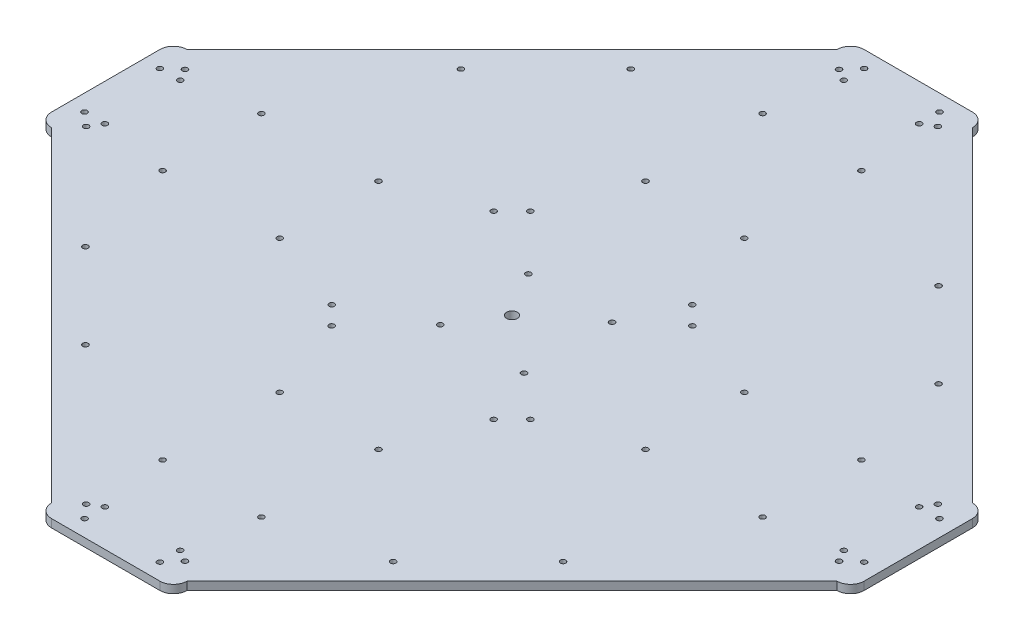
SolidWorks part; units mm, degrees
material "Acrylic (Medium-high impact)"
ref_plane "Front" through (0, 0, 0) normal (0, 0, 1) x (1, 0, 0)
ref_plane "Top" through (0, 0, 0) normal (0, 1, 0) x (1, 0, 0)
ref_plane "Right" through (0, 0, 0) normal (1, 0, 0) x (0, 0, -1)
sketch "Sketch1" plane through (0, 0, 0) normal (0, 1, 0) x (1, 0, 0)
  line L0 (-110, 50) -> (-300, 50)
  line L1 (280, -50) -> (90, -50)
  line L2 (290, -40) -> (290, 40)
  line L3 (280, 50) -> (90, 50)
  line L4 (-310, -40) -> (-310, 40)
  line L5 (-60, 100) -> (-110, 50)
  line L6 (90, 50) -> (40, 100)
  line L7 (30, -300) -> (-50, -300)
  line L8 (40, -290) -> (40, -100)
  line L9 (30, 300) -> (-50, 300)
  line L10 (-60, -290) -> (-60, -100)
  line L11 (90, -50) -> (40, -100)
  line L12 (-60, -100) -> (-110, -50)
  line L16 (-110, -50) -> (-300, -50)
  line L18 (40, 100) -> (40, 290)
  line L19 (-60, 100) -> (-60, 290)
  arc A0 (-50, 300) -> (-60, 290) centre (-50, 290) ccw
  arc A1 (40, 290) -> (30, 300) centre (30, 290) ccw
  arc A2 (290, 40) -> (280, 50) centre (280, 40) ccw
  arc A3 (280, -50) -> (290, -40) centre (280, -40) ccw
  arc A4 (30, -300) -> (40, -290) centre (30, -290) ccw
  arc A5 (-50, -300) -> (-60, -290) centre (-50, -290) cw
  arc A6 (-300, -50) -> (-310, -40) centre (-300, -40) cw
  arc A7 (-300, 50) -> (-310, 40) centre (-300, 40) ccw
  point P0 (0, 0)
  point P1 (8.4315, 46.1032)
  point P2 (128.4315, 46.1032)
  point P3 (8.4315, -56.5685)
  point P4 (128.4315, -56.5685)
  point P5 (0, 0)
  point P10 (0, 0)
  point P15 (-60, -50)
  point P17 (-60, 50)
  point P18 (-56.5685, -56.5685)
  point P23 (56.5685, 56.5685)
  point P25 (40, -50)
  point P28 (40, 50)
  point P31 (-60, 300)
  point P34 (40, 300)
  point P37 (290, 50)
  point P43 (40, -300)
  point P48 (-310, -50)
  point P51 (-310, 50)
  dimension "D1" = 600
  dimension "D5" = 10
  dimension "D2" = 100
  dimension "D3" = 100
  dimension "D4" = 600
  dimension "D6" = 190
  dimension "D7" = 190
  dimension "D8" = 190
  dimension "D9" = 190
extrude "Boss-Extrude1" add sketch "Sketch1" along normal blind 6
sketch "Sketch4" plane through (0, 6, 0) normal (0, 1, 0) x (1, 0, 0)
  line L0 (-10, 300) -> (-10, -432.1332) construction
  line L1 (30, 300) -> (-50, 300) construction
  line L2 (-338.2481, 0) -> (378.576, 0) construction
  circle A0 centre (-10, 0) radius 0.4957
extrude "Cut-Extrude3" cut sketch "Sketch4" against normal blind 10
sketch "Sketch5" plane through (0, 6, 0) normal (0, 1, 0) x (1, 0, 0)
  line L0 (-300, 50) -> (-60, 290)
  line L1 (-250, 50) -> (-60, 240)
  line L2 (-110, 50) -> (-300, 50) construction
  line L3 (-60, 100) -> (-60, 290) construction
  line L4 (-60, 240) -> (-60, 290)
  line L5 (-250, 50) -> (-300, 50)
  line L6 (40, 290) -> (280, 50)
  line L7 (280, 50) -> (230, 50)
  line L8 (230, 50) -> (40, 240)
  line L9 (40, 240) -> (40, 290)
  line L10 (280, -50) -> (40, -290)
  line L11 (40, -290) -> (40, -240)
  line L12 (40, -240) -> (230, -49.078)
  line L13 (230, -49.078) -> (280, -50)
  line L14 (-300, -50) -> (-60, -290)
  line L15 (-60, -290) -> (-60, -240)
  line L16 (-60, -240) -> (-250, -50)
  line L17 (-250, -50) -> (-300, -50)
  point P25 (-10, 2)
  dimension "D1" = 50
  dimension "D2" = 50
  dimension "D3" = 50
  dimension "D4" = 50
  dimension "D5" = 50
  dimension "D6" = 50
  dimension "D7" = 50
  dimension "D8" = 50
extrude "Boss-Extrude3" add sketch "Sketch5" against normal blind 6
sketch "Sketch6" plane through (0, 6, 0) normal (0, 1, 0) x (1, 0, 0)
  circle A0 centre (-37.8241, 287.837) radius 2
  circle A1 centre (-37.8241, 272.837) radius 2
  circle A4 centre (-46.4831, 221.5369) radius 2
  circle A5 centre (-46.4831, 135.0679) radius 2
  circle A6 centre (-69.8176, 73.3345) radius 2
  circle A7 centre (49.8176, 73.3345) radius 2
  circle A8 centre (26.4831, 135.0679) radius 2
  circle A9 centre (26.4831, 221.5369) radius 2
  circle A10 centre (191.3604, 113.6396) radius 2
  circle A11 centre (128.6396, 176.3604) radius 2
  circle A12 centre (17.8241, 272.837) radius 2
  circle A13 centre (17.8241, 287.837) radius 2
  circle A14 centre (-10, 0) radius 4
  dimension "D1" = 4
  dimension "D2" = 4
  dimension "D4" = 8
  dimension "D8" = 4
  dimension "D9" = 4
  dimension "D10" = 4
  dimension "D3" = 15
extrude "Cut-Extrude4" cut sketch "Sketch6" against normal blind 12
pattern_circular "CirPattern1" count 4 over 360 about axis through (-10, 0, 0) along (0, 1, 0) of "Cut-Extrude4"
sketch "Sketch7" plane through (0, 6, 0) normal (0, 1, 0) x (1, 0, 0)
  line L0 (40, 240) -> (230, 50) construction
  line L1 (40, 100) -> (40, 240) construction
  line L2 (90, 50) -> (40, 100) construction
  line L3 (230, 50) -> (90, 50) construction
  line L4 (90, -50) -> (229.0824, -50) construction
  line L5 (229.0824, -50) -> (40, -240) construction
  line L6 (40, -100) -> (90, -50) construction
  line L7 (40, -240) -> (40, -100) construction
  line L8 (-60, 240) -> (-60, 100) construction
  line L9 (-250, 50) -> (-60, 240) construction
  line L10 (-60, 100) -> (-110, 50) construction
  line L11 (-110, 50) -> (-250, 50) construction
  line L12 (-110, -50) -> (-60, -100) construction
  line L13 (-250, -50) -> (-110, -50) construction
  line L14 (-60, -240) -> (-250, -50) construction
  line L15 (-60, -100) -> (-60, -240) construction
  line L16 (40, 240) -> (230, 50)
  line L17 (40, 100) -> (40, 240)
  line L18 (90, 50) -> (40, 100)
  line L19 (230, 50) -> (90, 50)
  line L20 (90, -50) -> (229.0824, -50)
  line L21 (229.0824, -50) -> (40, -240)
  line L22 (40, -100) -> (90, -50)
  line L23 (40, -240) -> (40, -100)
  line L24 (-60, 240) -> (-60, 100)
  line L25 (-250, 50) -> (-60, 240)
  line L26 (-60, 100) -> (-110, 50)
  line L27 (-110, 50) -> (-250, 50)
  line L28 (-110, -50) -> (-60, -100)
  line L29 (-250, -50) -> (-110, -50)
  line L30 (-60, -240) -> (-250, -50)
  line L31 (-60, -100) -> (-60, -240)
extrude "Boss-Extrude4" add sketch "Sketch7" against normal up to surface (6 mm away) up to face at (63.3345, 0, -57.8176)
sketch "Sketch8" plane through (0, 0, 0) normal (0, -1, 0) x (-1, 0, 0)
  circle A0 centre (-279, 20) radius 2.5
  circle A1 centre (-279, -20) radius 2.5
extrude "Cut-Extrude5" [suppressed] cut sketch "Sketch8" against normal blind 144
pattern_circular "CirPattern2" [suppressed] count 4 over 360
sketch "Sketch9" plane through (0, 0, 0) normal (0, -1, 0) x (-1, 0, 0)
  circle A0 centre (-255, -20) radius 2.5
  circle A1 centre (-255, 20) radius 2.5
extrude "Cut-Extrude6" [suppressed] cut sketch "Sketch9" against normal blind 144
pattern_circular "CirPattern3" [suppressed] count 4 over 360
sketch "Sketch10" plane through (0, 6, 0) normal (0, 1, 0) x (1, 0, 0)
  line L0 (-310, 40) -> (-310, -40) construction
  line L1 (-50, -300) -> (30, -300) construction
  point P0 (-57, 33)
  point P1 (37, 33)
  point P2 (-57, -33)
  point P3 (37, -33)
  dimension "D1" = 94
  dimension "D2" = 66
  dimension "D3" = 253
  dimension "D4" = 267
ref_plane "Plane1" through (-10, 0, 0) normal (1, 0, 0) x (0, 0, -1)
ref_plane "Plane2" through (0, 0, 0) normal (0, 0, 1) x (1, 0, 0)
ref_plane "Plane3" through (-10, 0, 0) normal (-1, 0, 0) x (0, 0, 1)
sketch "Sketch11" plane through (0, 6, 0) normal (0, 1, 0) x (1, 0, 0)
  point P0 (32.7129, 23.7813)
  point P1 (-226.182, -59.3281)
  point P3 (-30.4306, -32.5)
  point P4 (31.3831, -32.5)
  point P6 (-29.1008, 23.7813)
sketch "Sketch23" plane through (0, 0, 0) normal (0, -1, 0) x (1, 0, 0)
  point P0 (-10, -24.0416)
  point P1 (-34.0416, 0)
  point P2 (-10, 24.0416)
  point P3 (14.0416, 0)
hole_wizard "Ø4.0mm Dowel Hole3" [suppressed] positions "Sketch26" profile "Sketch27" hole size "Ø4.0" standard "ANSI Metric"
sketch "Sketch26" plane through (0, 4, 0) normal (0, 1, 0) x (1, 0, 0)
  point P0 (-10, 24.0416)
  point P2 (-34.0416, 0)
  point P4 (14.0416, 0)
  point P6 (-10, -24.0416)
sketch "Sketch27" plane through (-10, 4, -24.0416) normal (1, 0, 0) x (0, 0, 1)
  line L0 (0, 0) -> (0, 99.5117)
  line L1 (0, 99.5117) -> (2, 98.31)
  line L2 (2, 98.31) -> (2, 0)
  line L5 (2, 0) -> (0, 0)
  line L10 (0, 99.5117) -> (-2, 98.31) construction
  line L11 (0, -6.35) -> (0, 107.95) construction
  dimension "Hole Dia." = 4
  dimension "Hole Depth" = 98.31
  dimension "Drill Angle" = 118
ref_plane "Plane4" through (-10, 0, 0) normal (-1, 0, 0) x (0, 0, 1)
sketch "Sketch28" plane through (0, 0, 0) normal (0, -1, 0) x (1, 0, 0)
  point P0 (-288, 36.4831)
  point P1 (-288, -36.4831)
  point P2 (-46.4831, -278)
  point P3 (26.4831, -278)
  point P4 (268, -36.4831)
  point P5 (268, 36.4831)
  point P6 (-46.4831, 278)
  point P7 (26.4831, 278)
hole_wizard "Ø4.0mm Dowel Hole4" positions "Sketch29" profile "Sketch30" hole size "Ø4.0" standard "ANSI Metric"
sketch "Sketch29" plane through (0, 0, 0) normal (0, -1, 0) x (-1, 0, 0)
  point P0 (46.4831, -278)
  point P3 (-26.4831, -278)
  point P6 (-268, -36.4831)
  point P9 (-268, 36.4831)
  point P12 (-26.4831, 278)
  point P15 (46.4831, 278)
  point P18 (288, 36.4831)
  point P21 (288, -36.4831)
sketch "Sketch30" plane through (-46.4831, 0, 278) normal (1, 0, 0) x (0, 0, -1)
  line L0 (0, 0) -> (0, 99.5117)
  line L1 (0, 99.5117) -> (2, 98.31)
  line L2 (2, 98.31) -> (2, 0)
  line L5 (2, 0) -> (0, 0)
  line L10 (0, 99.5117) -> (-2, 98.31) construction
  line L11 (0, -6.35) -> (0, 107.95) construction
  dimension "Hole Dia." = 4
  dimension "Hole Depth" = 98.31
  dimension "Drill Angle" = 118
ref_plane "Plane5" through (-10, 0, 0) normal (1, 0, 0) x (0, 0, -1)
sketch "Sketch31" plane through (0, 6, 0) normal (0, 1, 0) x (1, 0, 0)
  point P0 (31.3831, -32.5)
  point P1 (-30.4306, -32.5)
  point P2 (-30.4306, 32.5)
  point P3 (31.3831, 32.5)
hole_wizard "Ø4.0mm Dowel Hole5" positions "Sketch32" profile "Sketch33" hole size "Ø4.0" standard "ANSI Metric"
sketch "Sketch32" plane through (0, 6, 0) normal (0, 1, 0) x (1, 0, 0)
  point P0 (-30.4306, -32.5)
  point P3 (31.3831, -32.5)
  point P6 (31.3831, 32.5)
  point P9 (-30.4306, 32.5)
sketch "Sketch33" plane through (-30.4306, 6, 32.5) normal (1, 0, 0) x (0, 0, 1)
  line L0 (0, 0) -> (0, 99.5117)
  line L1 (0, 99.5117) -> (2, 98.31)
  line L2 (2, 98.31) -> (2, 0)
  line L5 (2, 0) -> (0, 0)
  line L10 (0, 99.5117) -> (-2, 98.31) construction
  line L11 (0, -6.35) -> (0, 107.95) construction
  dimension "Hole Dia." = 4
  dimension "Hole Depth" = 98.31
  dimension "Drill Angle" = 118
